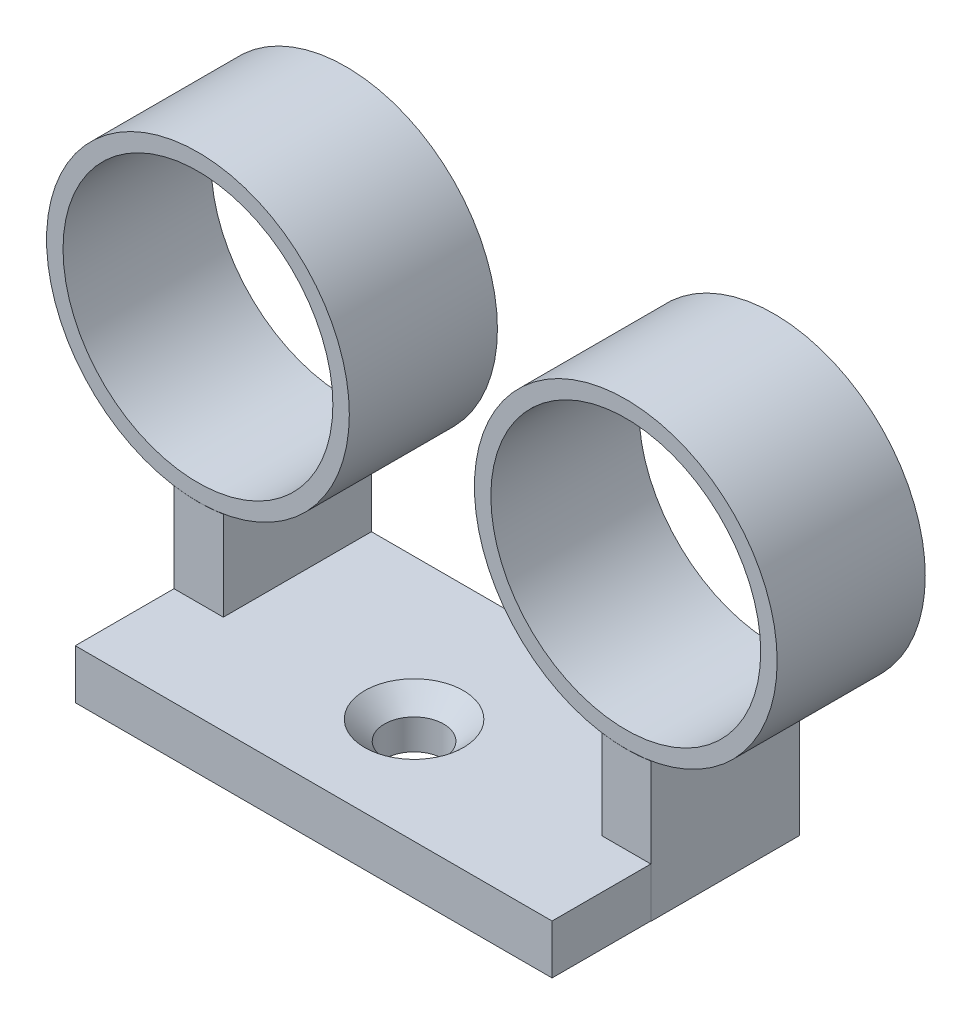
SolidWorks part; units mm, degrees
ref_plane "Alzado" through (0, 0, 0) normal (0, 0, 1) x (1, 0, 0)
ref_plane "Planta" through (0, 0, 0) normal (0, 1, 0) x (1, 0, 0)
ref_plane "Vista lateral" through (0, 0, 0) normal (1, 0, 0) x (0, 0, -1)
sketch "Sketch1" plane through (0, 0, 0) normal (0, 0, 1) x (1, 0, 0)
  circle A2 centre (1.4562, 17.9431) radius 8.2
  circle A3 centre (1.4562, 17.9431) radius 9.2
  circle A4 centre (27.4562, 17.9431) radius 8.2
  circle A5 centre (27.4562, 17.9431) radius 9.2
  dimension "D3" = 18.4
  dimension "D4" = 16.4
  dimension "D1" = 18.4
  dimension "D2" = 16.4
  dimension "D5" = 26
extrude "Boss-Extrude1" add sketch "Sketch1" along normal blind 9
sketch "Sketch2" plane through (0, 0, 0) normal (0, 0, 1) x (1, 0, 0)
  line L1 (0, 0.4391) -> (3, 0.4391)
  line L2 (0, 0.4391) -> (0, 8.8591)
  line L4 (3, 0.4391) -> (3, 8.8591)
  arc A1 (0, 8.8591) -> (3, 8.8591) centre (1.5, 18.0415) ccw
  point P4 (0, 0)
  dimension "D1" = 8.42
  dimension "D2" = 3
sketch "Sketch3" plane through (0, 0, 0) normal (0, 0, 1) x (1, 0, 0)
  line L1 (26, 0.4391) -> (29, 0.4391)
  line L2 (26, 0.4391) -> (26, 8.8591)
  line L4 (29, 0.4391) -> (29, 8.8591)
  arc A1 (26, 8.8591) -> (29, 8.8591) centre (27.5, 18.0415) ccw
  point P4 (0, 0)
  point P5 (0, 0)
  dimension "D1" = 8.42
  dimension "D2" = 3
extrude "Boss-Extrude2" add sketch "Sketch2" along normal blind 9 separate body
extrude "Boss-Extrude3" add sketch "Sketch3" along normal blind 9 separate body
sketch "Sketch4" plane through (0, 0.4391, 0) normal (0, -1, 0) x (-1, 0, 0)
  line L1 (0, 0) -> (-28.9774, 0)
  line L2 (0, 0) -> (0, -15)
  line L3 (0, -15) -> (-28.9774, -15)
  line L4 (-28.9774, 0) -> (-28.9774, -15)
  dimension "D1" = 15
extrude "Boss-Extrude4" add sketch "Sketch4" against normal blind 3
hole_wizard "Avellanado para tornillo con cabeza avellanada en cruz de M31" positions "3DSketch1" profile "Sketch5" countersink size "M3" standard "AS"
sketch3d "3DSketch1"
  point P0 (14.1563, 3.4391, 8.5662)
sketch "Sketch5" plane through (14.1563, 3.4391, 8.5662) normal (1, 0, 0) x (0, 0, 1)
  line L0 (0, 0) -> (0, 11.0815)
  line L1 (0, 11.0815) -> (1.8, 10)
  line L2 (1.8, 10) -> (1.8, 1.1588)
  line L3 (1.8, 1.1588) -> (3, 0)
  line L5 (3, 0) -> (0, 0)
  line L6 (-1.8, 1.1588) -> (-3, 0) construction
  line L10 (0, 11.0815) -> (-1.8, 10) construction
  line L11 (0, -6.35) -> (0, 107.95) construction
  dimension "Diámetro de taladro" = 3.6
  dimension "Profundidad de taladro" = 10
  dimension "Ángulo de avellanado cercano" = 6
  dimension "Ángulo de avellanado lejano" = 92
  dimension "Ángulo de perforador" = 118
